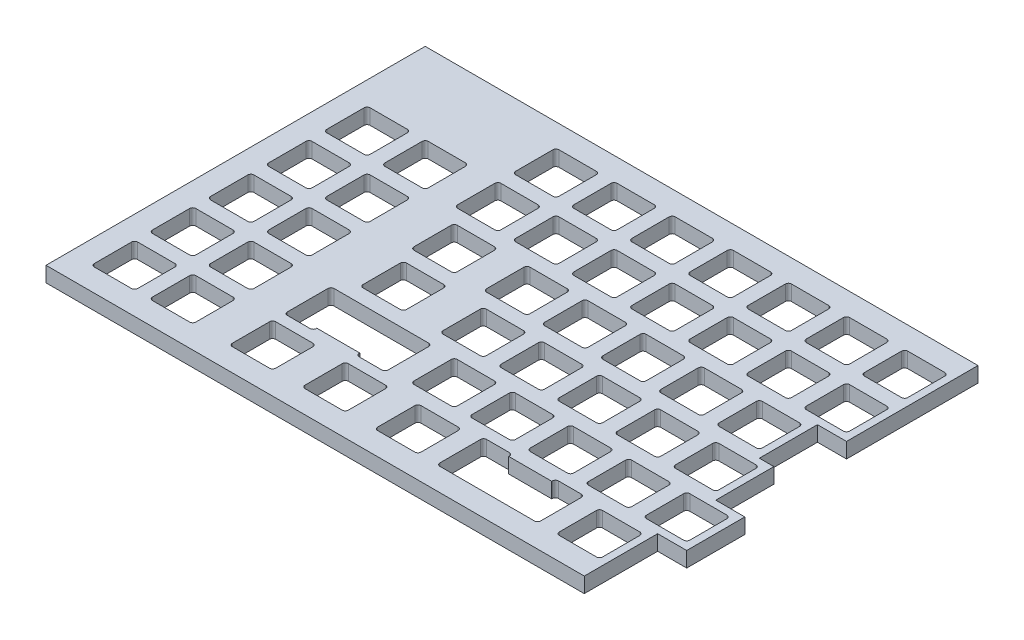
SolidWorks part; units mm, degrees
ref_plane "Front Plane" through (0, 0, 0) normal (0, 0, 1) x (1, 0, 0)
ref_plane "Top Plane" through (0, 0, 0) normal (0, 1, 0) x (1, 0, 0)
ref_plane "Right Plane" through (0, 0, 0) normal (1, 0, 0) x (0, 0, -1)
sketch "Sketch1" plane through (0, 0, 0) normal (0, 1, 0) x (1, 0, 0)
  line L0 (0, 0) -> (0, 124.3)
  line L1 (0, 124.3) -> (181.2125, 124.3)
  line L2 (181.2125, 124.3) -> (181.2125, 81.2)
  line L3 (181.2125, 81.2) -> (171.6875, 81.2)
  line L4 (171.6875, 81.2) -> (171.6875, 62.15)
  line L5 (171.6875, 62.15) -> (176.45, 62.15)
  line L6 (176.45, 62.15) -> (176.45, 43.1)
  line L7 (176.45, 43.1) -> (185.975, 43.1)
  line L8 (185.975, 43.1) -> (185.975, 24.05)
  line L9 (185.975, 24.05) -> (176.45, 24.05)
  line L10 (176.45, 24.05) -> (176.45, 0)
  line L11 (176.45, 0) -> (0, 0)
  dimension "D2" = 181.2125
  dimension "D3" = 43.1
  dimension "D4" = 4.7625
  dimension "D5" = 9.525
  dimension "D6" = 19.05
  dimension "D1" = 24.05
extrude "Plate Frame" add sketch "Sketch1" along normal blind 5
sketch "Sketch4" plane through (0, 5, 0) normal (0, 1, 0) x (1, 0, 0)
  line L0 (14.525, 90.725) -> (33.575, 90.725) construction
  line L1 (33.575, 90.725) -> (33.575, 71.675) construction
  line L2 (33.575, 71.675) -> (33.575, 52.625) construction
  line L3 (33.575, 52.625) -> (33.575, 33.575) construction
  line L4 (33.575, 33.575) -> (33.575, 14.525) construction
  line L5 (33.575, 14.525) -> (14.525, 14.525) construction
  line L6 (14.525, 14.525) -> (14.525, 33.575) construction
  line L7 (14.525, 33.575) -> (14.525, 52.625) construction
  line L8 (14.525, 52.625) -> (14.525, 71.675) construction
  line L9 (14.525, 71.675) -> (14.525, 90.725) construction
  line L10 (14.525, 71.675) -> (33.575, 71.675) construction
  line L11 (14.525, 52.625) -> (33.575, 52.625) construction
  line L12 (14.525, 33.575) -> (33.575, 33.575) construction
  line L13 (57.3875, 109.775) -> (57.3875, 90.725) construction
  line L14 (57.3875, 90.725) -> (76.4375, 90.725) construction
  line L15 (76.4375, 90.725) -> (76.4375, 109.775) construction
  line L16 (76.4375, 109.775) -> (95.4875, 109.775) construction
  line L17 (95.4875, 109.775) -> (114.5375, 109.775) construction
  line L18 (114.5375, 109.775) -> (133.5875, 109.775) construction
  line L19 (133.5875, 109.775) -> (152.6375, 109.775) construction
  line L20 (152.6375, 109.775) -> (171.6875, 109.775) construction
  line L21 (171.6875, 109.775) -> (171.6875, 90.725) construction
  line L22 (171.6875, 90.725) -> (152.6375, 90.725) construction
  line L23 (152.6375, 90.725) -> (133.5875, 90.725) construction
  line L24 (133.5875, 90.725) -> (114.5375, 90.725) construction
  line L25 (114.5375, 90.725) -> (95.4875, 90.725) construction
  line L26 (95.4875, 90.725) -> (76.4375, 90.725) construction
  line L27 (57.3875, 109.775) -> (76.4375, 109.775) construction
  line L28 (95.4875, 109.775) -> (95.4875, 90.725) construction
  line L29 (114.5375, 90.725) -> (114.5375, 109.775) construction
  line L30 (133.5875, 109.775) -> (133.5875, 90.725) construction
  line L31 (152.6375, 90.725) -> (152.6375, 109.775) construction
  line L32 (62.15, 71.675) -> (85.9625, 71.675) construction
  line L33 (85.9625, 71.675) -> (105.0125, 71.675) construction
  line L34 (105.0125, 71.675) -> (124.0625, 71.675) construction
  line L35 (124.0625, 71.675) -> (143.1125, 71.675) construction
  line L36 (143.1125, 71.675) -> (162.1625, 71.675) construction
  line L37 (90.725, 52.625) -> (109.775, 52.625) construction
  line L38 (109.775, 52.625) -> (128.825, 52.625) construction
  line L39 (128.825, 52.625) -> (147.875, 52.625) construction
  line L40 (147.875, 52.625) -> (166.925, 52.625) construction
  line L41 (100.25, 33.575) -> (119.3, 33.575) construction
  line L42 (119.3, 33.575) -> (138.35, 33.575) construction
  line L43 (138.35, 33.575) -> (157.4, 33.575) construction
  line L44 (157.4, 33.575) -> (176.45, 33.575) construction
  line L45 (171.6875, 71.675) -> (162.1625, 71.675) construction
  line L46 (171.6875, 62.15) -> (171.6875, 81.2) construction
  line L49 (59.7687, 14.525) -> (83.5812, 14.525) construction
  line L50 (83.5812, 14.525) -> (107.3937, 14.525) construction
  line L51 (64.5312, 52.625) -> (90.725, 52.625) construction
  line L52 (107.3937, 14.525) -> (166.925, 14.525) construction
  point P0 (14.525, 14.525)
  point P1 (33.575, 14.525)
  point P2 (33.575, 33.575)
  point P3 (14.525, 33.575)
  point P4 (14.525, 52.625)
  point P5 (33.575, 52.625)
  point P6 (33.575, 71.675)
  point P7 (14.525, 71.675)
  point P8 (14.525, 90.725)
  point P9 (33.575, 90.725)
  point P12 (57.3875, 109.775)
  point P21 (57.3875, 90.725)
  point P22 (76.4375, 90.725)
  point P23 (76.4375, 109.775)
  point P24 (95.4875, 109.775)
  point P25 (95.4875, 90.725)
  point P26 (114.5375, 90.725)
  point P27 (114.5375, 109.775)
  point P28 (133.5875, 109.775)
  point P29 (133.5875, 90.725)
  point P30 (152.6375, 90.725)
  point P31 (152.6375, 109.775)
  point P32 (171.6875, 109.775)
  point P33 (171.6875, 90.725)
  point P44 (85.9625, 71.675)
  point P49 (62.15, 71.675)
  point P50 (105.0125, 71.675)
  point P51 (124.0625, 71.675)
  point P52 (143.1125, 71.675)
  point P53 (162.1625, 71.675)
  point P54 (90.725, 52.625)
  point P55 (109.775, 52.625)
  point P56 (128.825, 52.625)
  point P57 (147.875, 52.625)
  point P58 (166.925, 52.625)
  point P59 (100.25, 33.575)
  point P60 (119.3, 33.575)
  point P61 (138.35, 33.575)
  point P62 (157.4, 33.575)
  point P63 (176.45, 33.575)
  point P81 (83.5812, 14.525)
  point P82 (107.3937, 14.525)
  point P83 (64.5312, 52.625)
  point P90 (166.925, 14.525)
  point P94 (59.7687, 14.525)
  dimension "D1" = 19.05
  dimension "D2" = 9.525
  dimension "D3" = 23.8125
  dimension "D4" = 23.8125
  dimension "D6" = 9.525
  dimension "D5" = 4.7625
  dimension "D7" = 9.525
  dimension "D8" = 23.8125
  dimension "D9" = 26.1938
  dimension "D10" = 26.1938
  dimension "D11" = 59.5312
sketch "Sketch2" plane through (0, 5, 0) normal (0, 1, 0) x (1, 0, 0)
  line L0 (7.425, 8.425) -> (7.425, 20.625)
  line L1 (8.425, 21.625) -> (20.625, 21.625)
  line L2 (21.625, 20.625) -> (21.625, 8.425)
  line L3 (20.625, 7.425) -> (8.425, 7.425)
  line L4 (8.425, 21.625) -> (20.625, 7.425) construction
  arc A0 (7.425, 20.625) -> (8.425, 21.625) centre (8.425, 20.625) cw
  arc A1 (20.625, 21.625) -> (21.625, 20.625) centre (20.625, 20.625) cw
  arc A2 (21.625, 8.425) -> (20.625, 7.425) centre (20.625, 8.425) cw
  arc A3 (8.425, 7.425) -> (7.425, 8.425) centre (8.425, 8.425) cw
  point P12 (14.525, 14.525)
  dimension "D3" = 1
  dimension "D1" = 14.2
extrude "1U" cut sketch "Sketch2" against normal through all
pattern_sketch "Sketch-Pattern1" of "1U" driven by "Sketch4"
sketch "Sketch5" plane through (0, 5, 0) normal (0, 1, 0) x (1, 0, 0)
  line L0 (107.3937, 14.525) -> (166.925, 14.525) construction
  line L1 (69.2937, 33.575) -> (100.25, 33.575) construction
  point P0 (69.2937, 33.575)
  point P1 (137.1594, 14.525)
  point P4 (137.1594, 14.525)
  dimension "D1" = 30.9563
sketch "Sketch6" plane through (0, 5, 0) normal (0, 1, 0) x (1, 0, 0)
  line L0 (52.7937, 26.325) -> (52.7937, 39.625)
  line L1 (53.7937, 40.625) -> (84.7937, 40.625)
  line L2 (85.7937, 39.625) -> (85.7937, 26.325)
  line L3 (84.7937, 25.325) -> (77.3437, 25.325)
  line L5 (61.2437, 25.325) -> (53.7937, 25.325)
  line L6 (62.2437, 26.325) -> (62.2437, 26.525)
  line L7 (62.2437, 26.525) -> (76.3437, 26.525)
  line L8 (76.3437, 26.525) -> (76.3437, 26.325)
  line L9 (62.2437, 26.525) -> (76.3437, 40.625) construction
  arc A0 (52.7937, 39.625) -> (53.7937, 40.625) centre (53.7937, 39.625) cw
  arc A1 (84.7937, 40.625) -> (85.7937, 39.625) centre (84.7937, 39.625) cw
  arc A2 (85.7937, 26.325) -> (84.7937, 25.325) centre (84.7937, 26.325) cw
  arc A3 (77.3437, 25.325) -> (76.3437, 26.325) centre (77.3437, 26.325) cw
  arc A4 (62.2437, 26.325) -> (61.2437, 25.325) centre (61.2437, 26.325) cw
  arc A5 (53.7937, 25.325) -> (52.7937, 26.325) centre (53.7937, 26.325) cw
  point P23 (69.2937, 33.575)
  dimension "D1" = 1
  dimension "D2" = 14.1
  dimension "D3" = 33
  dimension "D4" = 14.1
  dimension "D5" = 15.3
sketch "Sketch7" plane through (0, 5, 0) normal (0, 1, 0) x (1, 0, 0)
  line L10 (121.6594, 7.475) -> (152.6594, 7.475)
  line L11 (153.6594, 8.475) -> (153.6594, 21.775)
  line L12 (152.6594, 22.775) -> (145.2094, 22.775)
  line L13 (144.2094, 21.775) -> (144.2094, 21.575)
  line L14 (144.2094, 21.575) -> (130.1094, 21.575)
  line L15 (130.1094, 21.575) -> (130.1094, 21.775)
  line L16 (129.1094, 22.775) -> (121.6594, 22.775)
  line L17 (120.6594, 21.775) -> (120.6594, 8.475)
  line L18 (144.2094, 21.575) -> (130.1094, 7.475) construction
  arc A6 (152.6594, 7.475) -> (153.6594, 8.475) centre (152.6594, 8.475) ccw
  arc A7 (153.6594, 21.775) -> (152.6594, 22.775) centre (152.6594, 21.775) ccw
  arc A8 (145.2094, 22.775) -> (144.2094, 21.775) centre (145.2094, 21.775) ccw
  arc A10 (121.6594, 22.775) -> (120.6594, 21.775) centre (121.6594, 21.775) ccw
  arc A11 (120.6594, 8.475) -> (121.6594, 7.475) centre (121.6594, 8.475) ccw
  arc A12 (129.1094, 22.775) -> (130.1094, 21.775) centre (129.1094, 21.775) cw
  point P43 (137.1594, 14.525)
  dimension "D6" = 1
  dimension "D7" = 14.1
  dimension "D8" = 15.3
  dimension "D9" = 33
  dimension "D10" = 14.1
extrude "Cut-Extrude1" cut sketch "Sketch6" against normal through all
extrude "Cut-Extrude2" cut sketch "Sketch7" against normal through all
equation "\"D2@Sketch4\"=19.05/2"
equation "\"D3@Sketch4\"=19.05/2 + (19.05*1.5)/2"
equation "\"D4@Sketch4\"=19.05/2 + 19.05*.25 + 19.05/2"
equation "\"D6@Sketch4\"=19.05/2"
equation "\"D5@Sketch4\"=19.05/4"
equation "\"D7@Sketch4\"=19.05/2"
equation "\"D5@Sketch1\"=19.05/2"
equation "\"D4@Sketch1\"=19.05/4"
equation "\"D8@Sketch4\"=19.05*1.25"
equation "\"D9@Sketch4\"=19.05/2 + 19.05*1.75/2"
equation "\"D10@Sketch4\"=19.05/2 + 19.05*.25 + 19.05*1.25/2"
equation "\"D11@Sketch4\"=19.05*1.25/2 + 19.05*2 + 19.05/2"
equation "\"D1@Sketch5\"=19.05*2.25/2 + 19.05/2"
equation "\"D3@Sketch1\"=19.05*2 + 5"
equation "\"D1@Sketch1\"=19.05 + 5"
equation "\"D2@Sketch1\"=9.25*19.05 + 5"
